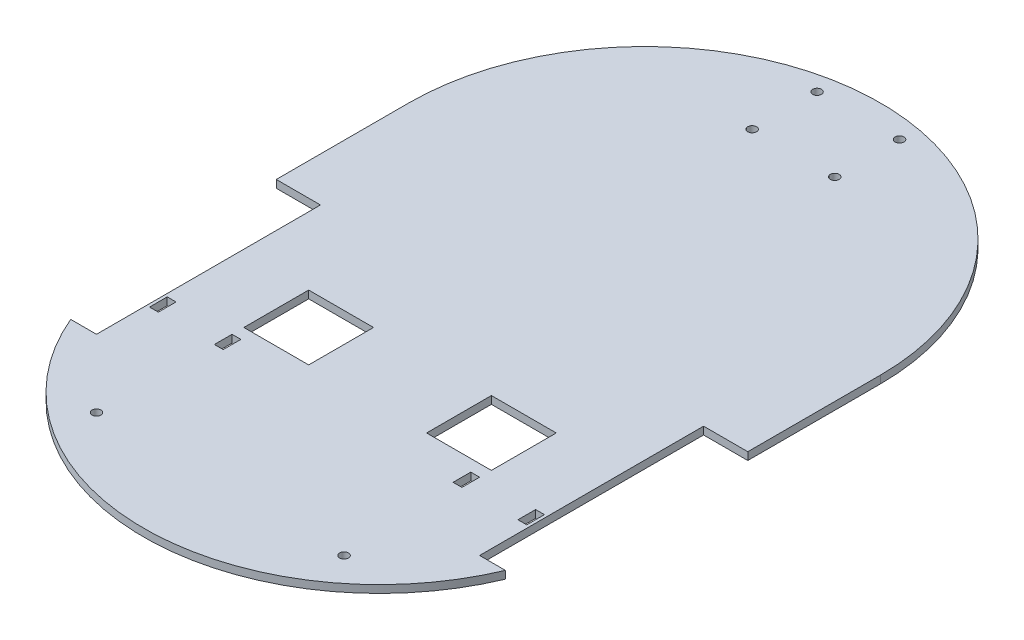
SolidWorks part; units mm, degrees
ref_plane "Płaszczyzna przednia" through (0, 0, 0) normal (0, 0, 1) x (1, 0, 0)
ref_plane "Płaszczyzna górna" through (0, 0, 0) normal (0, 1, 0) x (1, 0, 0)
ref_plane "Płaszczyzna prawa" through (0, 0, 0) normal (1, 0, 0) x (0, 0, -1)
sketch "Sketch2" plane through (0, 0, 0) normal (0, 1, 0) x (1, 0, 0)
  line L0 (0, -45) -> (0, 45) construction
  line L3 (-80, -45) -> (-80, 45)
  line L4 (80, -45) -> (80, 45)
  line L6 (65, 0) -> (103, 0)
  line L7 (65, 0) -> (65, -76)
  line L8 (65, -76) -> (103, -76)
  line L9 (103, 0) -> (103, -76)
  line L14 (103, -38) -> (31, -38) construction
  line L15 (20, -27) -> (42, -27)
  line L16 (20, -27) -> (20, -49)
  line L17 (20, -49) -> (42, -49)
  line L18 (42, -27) -> (42, -49)
  line L19 (20, -27) -> (42, -49) construction
  line L20 (20, -49) -> (42, -27) construction
  line L21 (0, -55) -> (0, 55) construction
  line L22 (42, -53) -> (39, -53)
  line L23 (42, -53) -> (42, -59)
  line L24 (42, -59) -> (39, -59)
  line L25 (39, -53) -> (39, -59)
  line L30 (61, -53) -> (64, -53)
  line L31 (61, -53) -> (61, -59)
  line L32 (61, -59) -> (64, -59)
  line L33 (64, -53) -> (64, -59)
  line L34 (-20, -49) -> (-42, -27) construction
  line L35 (-20, -27) -> (-42, -49) construction
  line L36 (-103, -38) -> (-31, -38) construction
  line L37 (-64, -53) -> (-64, -59)
  line L38 (-61, -59) -> (-64, -59)
  line L39 (-61, -53) -> (-61, -59)
  line L40 (-61, -53) -> (-64, -53)
  line L41 (-39, -53) -> (-39, -59)
  line L42 (-42, -59) -> (-39, -59)
  line L43 (-42, -53) -> (-42, -59)
  line L44 (-42, -53) -> (-39, -53)
  line L45 (-42, -27) -> (-42, -49)
  line L46 (-20, -49) -> (-42, -49)
  line L47 (-20, -27) -> (-20, -49)
  line L48 (-20, -27) -> (-42, -27)
  line L49 (-103, 0) -> (-103, -76)
  line L50 (-65, -76) -> (-103, -76)
  line L51 (-65, 0) -> (-65, -76)
  line L52 (-65, 0) -> (-103, 0)
  arc A4 (-80, -45) -> (80, -45) centre (0, -45) ccw
  arc A5 (80, 45) -> (-80, 45) centre (0, 45) ccw
  circle A6 centre (14, 117.5) radius 1.5
  circle A7 centre (14, 95.5) radius 1.5
  circle A8 centre (-14, 95.5) radius 1.5
  circle A9 centre (-14, 117.5) radius 1.5
  circle A10 centre (42, -99) radius 1.5
  circle A11 centre (-42, -99) radius 1.5
  point P3 (0, 0)
  point P8 (0, 125)
  point P9 (0, -125)
  point P22 (31, -38)
  point P61 (-31, -38)
  dimension "D19" = 3
  dimension "D20" = 3
  dimension "D23" = 3
  dimension "D1" = 250
  dimension "D2" = 160
  dimension "D3" = 76
  dimension "D4" = 65
  dimension "D5" = 0
  dimension "D6" = 38
  dimension "D7" = 22
  dimension "D8" = 23
  dimension "D9" = 22
  dimension "D10" = 4
  dimension "D11" = 3
  dimension "D12" = 6
  dimension "D13" = 23
  dimension "D14" = 6
  dimension "D15" = 3
  dimension "D16" = 19
  dimension "D17" = 4
  dimension "D18" = 22
  dimension "D21" = 14
  dimension "D22" = 7.5
  dimension "D24" = 40
  dimension "D25" = 42
extrude "Boss-Extrude2" add sketch "Sketch2" along normal blind 2.6 contours L4 A5 L3 L52 L51 L50 A4 L8 L7 L6 A8 A7 A6 L43 L44 L41 L42 L30 L33 L32 L31 L15 L18 L17 L16 L25 L22 L23 L24 L40 L39 L38 L37 L48 L47 L46 L45 A9
